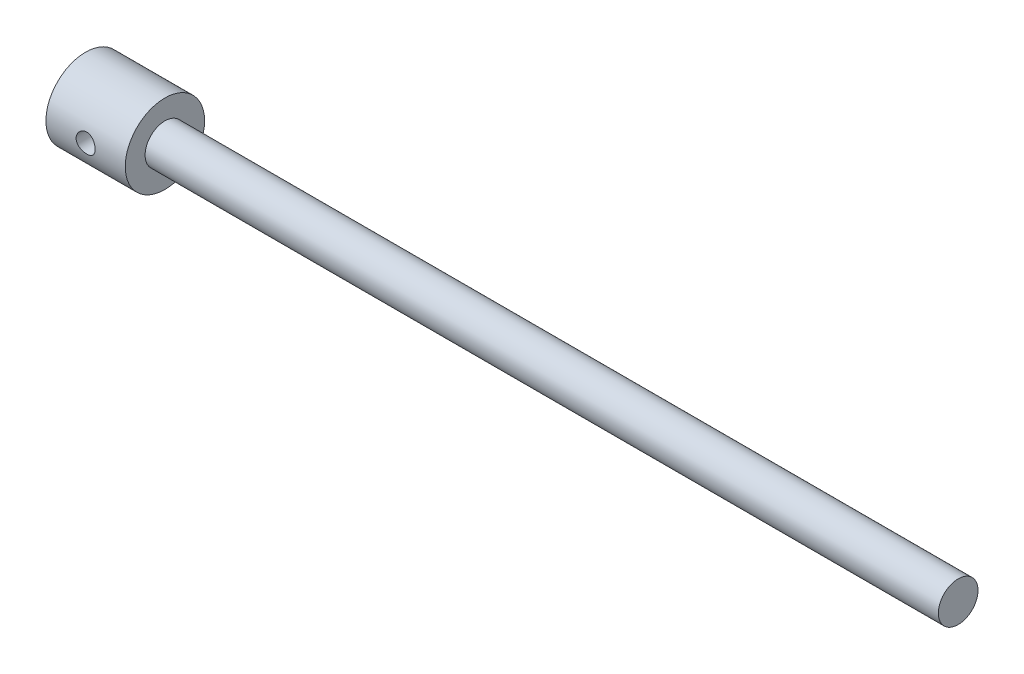
SolidWorks part; units mm, degrees
ref_plane "Front Plane" through (0, 0, 0) normal (0, 0, 1) x (1, 0, 0)
ref_plane "Top Plane" through (0, 0, 0) normal (0, 1, 0) x (1, 0, 0)
ref_plane "Right Plane" through (0, 0, 0) normal (1, 0, 0) x (0, 0, -1)
sketch "Sketch1" plane through (0, 0, 0) normal (1, 0, 0) x (0, 0, -1)
  circle A0 centre (0, 0) radius 25
  dimension "D1" = 50
extrude "Boss-Extrude1" add sketch "Sketch1" along normal blind 50
sketch "Sketch2" plane through (0, 0, 0) normal (0, 0, 1) x (1, 0, 0)
  circle A0 centre (25, 0) radius 6
  point P2 (0, 0)
  dimension "D1" = 12
  dimension "D2" = 25
extrude "Cut-Extrude1" cut sketch "Sketch2" against normal mid plane 70
sketch "Sketch3" plane through (50, 0, 0) normal (1, 0, 0) x (0, 0, -1)
  circle A0 centre (0, 0) radius 12.5
  dimension "D1" = 25
extrude "Boss-Extrude2" add sketch "Sketch3" along normal blind 500
cosmetic thread "Cosmetic Thread1" parameters "D2"=20.704
cosmetic thread "Cosmetic Thread2" parameters "D2"=20.704
